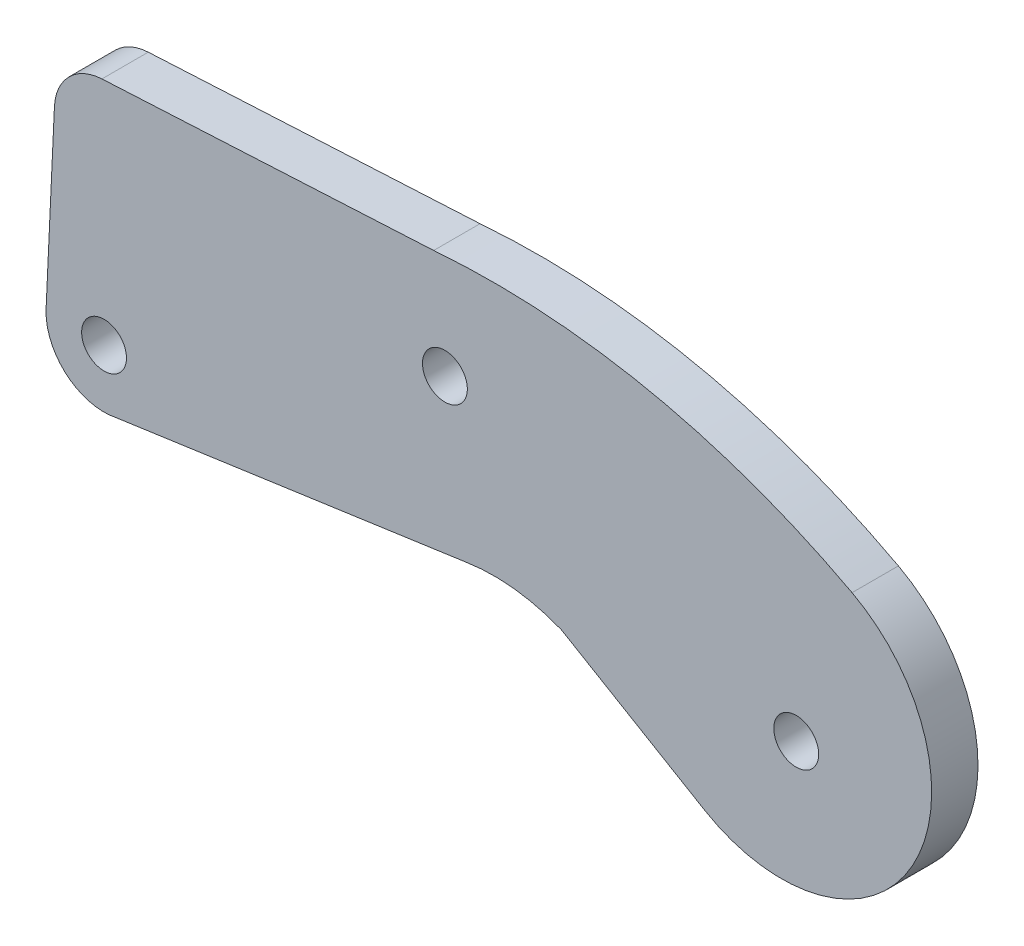
SolidWorks part; units mm, degrees
ref_plane "Front Plane" through (0, 0, 0) normal (0, 0, 1) x (1, 0, 0)
ref_plane "Top Plane" through (0, 0, 0) normal (0, 1, 0) x (1, 0, 0)
ref_plane "Right Plane" through (0, 0, 0) normal (1, 0, 0) x (0, 0, -1)
sketch "Sketch1" plane through (0, 0, 0) normal (0, 0, 1) x (1, 0, 0)
  line L0 (-44, -26.8) -> (2.7, -20.15)
  line L1 (15.6, -21.5997) -> (34.7684, -32.9201)
  line L4 (-52.2385, 5.1117) -> (-53.3664, -19.1383)
  line L5 (-45.8866, 11.5) -> (-1.5, 13.8188)
  circle A0 centre (47, -18.8) radius 3
  circle A1 centre (-45.6, -19.2) radius 3
  circle A2 centre (0, 0) radius 3
  arc A3 (-53.3664, -19.1383) -> (-44, -26.8) centre (-45.6, -19.2) ccw
  arc A4 (15.6, -21.5997) -> (2.7, -20.15) centre (6.5696, -43.836) ccw
  arc A8 (-45.8866, 11.5) -> (-52.2385, 5.1117) centre (-45.5366, 4.8) ccw
  arc A9 (34.7684, -32.9201) -> (54.4696, 2.1573) centre (45, -15.5954) ccw
  arc A10 (54.4696, 2.1573) -> (-1.5, 13.8188) centre (6.5541, -87.67) ccw
  arc A11 (58, 0.2) -> (-1.5, 13.8188) centre (6.3009, -88.8853) ccw construction
  arc A12 (-1.5, 13.8188) -> (-274.8783, -28.3238) centre (36.5716, -1140.9217) ccw construction
  dimension "D1" = 6
  dimension "D8" = 24
  dimension "D18" = 20.1204
  dimension "D2" = 20.15
  dimension "D3" = 2.7
  dimension "D4" = 44
  dimension "D5" = 26.8
  dimension "D6" = 12.9
  dimension "D7" = 21.5997
  dimension "D9" = 45
  dimension "D10" = 15.5954
  dimension "D11" = 45.6
  dimension "D12" = 19.2
  dimension "D13" = 18.8
  dimension "D14" = 47
  dimension "D15" = 24.25
  dimension "D16" = 24
  dimension "D17" = 30.7
extrude "Boss-Extrude1" add sketch "Sketch1" along normal blind 6.2
